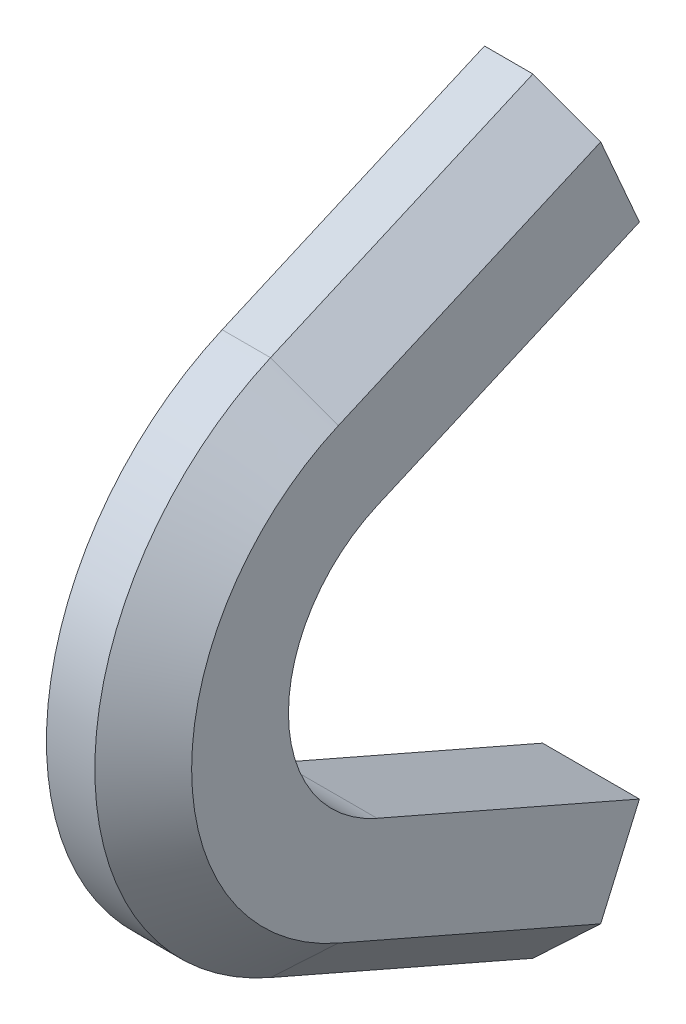
SolidWorks part; units mm, degrees
material "Q355"
ref_plane "前视基准面" through (0, 0, 0) normal (0, 0, 1) x (1, 0, 0)
ref_plane "上视基准面" through (0, 0, 0) normal (0, 1, 0) x (1, 0, 0)
ref_plane "右视基准面" through (0, 0, 0) normal (1, 0, 0) x (0, 0, -1)
sketch "草图1" plane through (0, 0, 0) normal (-1, 0, 0) x (0, 0, 1)
  line L0 (0, 0) -> (-36.3377, 0) construction
  line L1 (6.1004, 13.9767) -> (-21, 25.8053)
  line L2 (0, 0) -> (21.256, 0) construction
  line L3 (6.1004, -13.9767) -> (-21, -25.8053)
  line L4 (12.1009, -27.7242) -> (-14.9996, -39.5528)
  line L5 (12.1009, 27.7242) -> (-14.9996, 39.5528)
  line L6 (-14.9996, 39.5528) -> (-21, 25.8053)
  line L7 (-21, -25.8053) -> (-14.9996, -39.5528)
  arc A0 (6.1004, -13.9767) -> (6.1004, 13.9767) centre (0, 0) ccw
  arc A1 (12.1009, -27.7242) -> (12.1009, 27.7242) centre (0, 0) ccw
  dimension "D1" = 30.5
  dimension "D2" = 23.58
  dimension "D3" = 21
  dimension "D4" = 15
extrude "凸台-拉伸1" add sketch "草图1" along normal blind 10
chamfer "倒角1" distance 5 angle 45 3 edges at (0, -33.6385, -1.4493) (0, 33.6385, -1.4493) (0, 0, 30.25)
